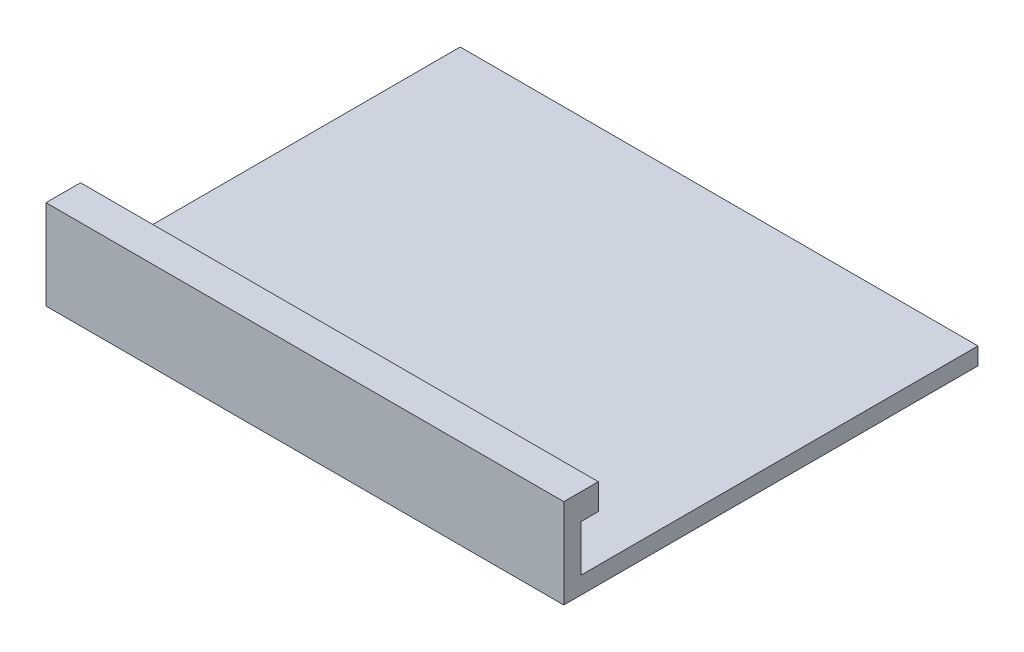
SolidWorks part; units mm, degrees
material "Ceramic Porcelain"
ref_plane "Front Plane" through (0, 0, 0) normal (0, 0, 1) x (1, 0, 0)
ref_plane "Top Plane" through (0, 0, 0) normal (0, 1, 0) x (1, 0, 0)
ref_plane "Right Plane" through (0, 0, 0) normal (1, 0, 0) x (0, 0, -1)
sketch "Sketch1" plane through (0, 0, 0) normal (1, 0, 0) x (0, 0, -1)
  line L0 (-584.2, 93.6625) -> (-584.2, 25.4)
  line L1 (-584.2, 25.4) -> (0, 25.4)
  line L2 (0, 25.4) -> (0, 0)
  line L3 (0, 0) -> (-609.6, 0)
  line L4 (-609.6, 0) -> (-609.6, 131.7625)
  line L5 (-609.6, 131.7625) -> (-558.8, 131.7625)
  line L6 (-558.8, 131.7625) -> (-558.8, 93.6625)
  line L7 (-558.8, 93.6625) -> (-584.2, 93.6625)
  dimension "D1" = 106.3625
  dimension "D2" = 68.2625
  dimension "D3" = 558.8
  dimension "D4" = 25.4
  dimension "D5" = 25.4
  dimension "D6" = 25.4
extrude "Boss-Extrude1" add sketch "Sketch1" along normal blind 762
